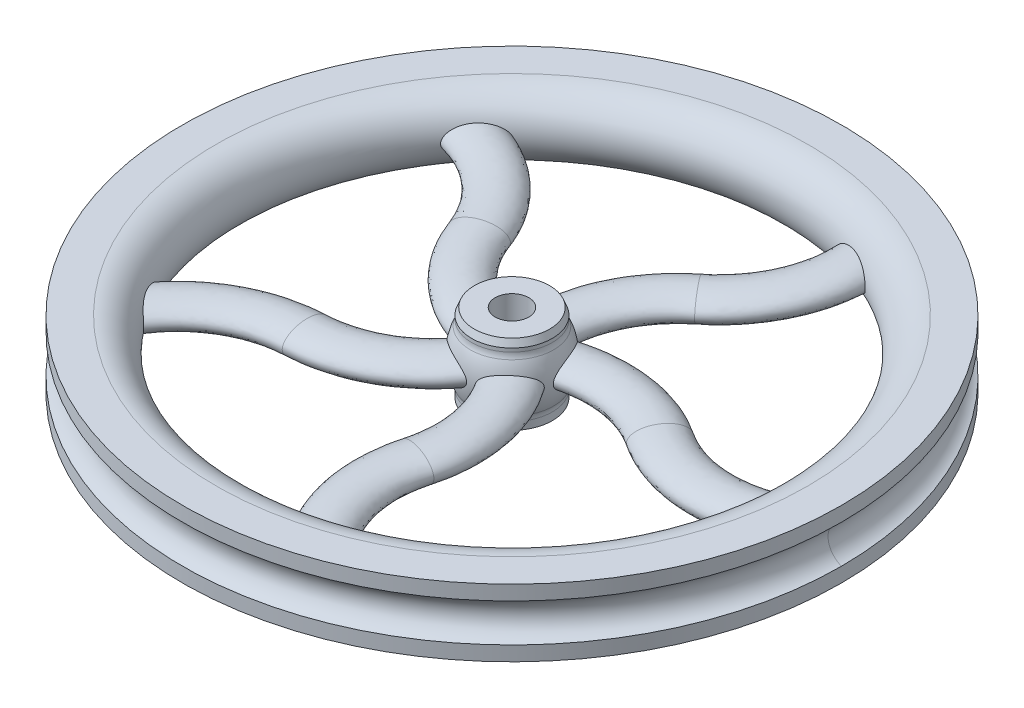
SolidWorks part; units mm, degrees
ref_plane "Front" through (0, 0, 0) normal (0, 0, 1) x (1, 0, 0)
ref_plane "Top" through (0, 0, 0) normal (0, 1, 0) x (1, 0, 0)
ref_plane "Right" through (0, 0, 0) normal (1, 0, 0) x (0, 0, -1)
sketch "Sketch1" plane through (0, 0, 0) normal (0, 0, 1) x (1, 0, 0)
  line L0 (30, -22.3607) -> (30, -30)
  line L5 (0, 30) -> (30, 30)
  line L6 (0, 30) -> (0, -30) construction
  line L7 (0, -30) -> (30, -30)
  line L8 (30, 30) -> (30, 22.3607)
  line L9 (0, 30) -> (0, -30) construction
  line L10 (0, 30) -> (0, -30)
  arc A0 (30.9524, 18.1015) -> (30.9524, -18.1015) centre (-7.5, 0) cw
  arc A1 (30.9524, -18.1015) -> (30, -22.3607) centre (40, -22.3607) ccw
  arc A2 (30.9524, 18.1015) -> (30, 22.3607) centre (40, 22.3607) cw
  point P10 (30, -20)
  point P13 (30, 20)
  dimension "D6" = 10
  dimension "D1" = 10
  dimension "D2" = 5
  dimension "D3" = 40
  dimension "D4" = 60
  dimension "D5" = 60
revolve "Hub" add sketch "Sketch1" angle 360 about L6
sketch "Sketch2" plane through (0, 0, 0) normal (0, 0, 1) x (1, 0, 0)
  line L0 (0, -1000) -> (0, 49000) construction
  line L1 (-1000, 0) -> (914.045, 0) construction
  line L2 (220, 0) -> (914.045, 0) construction
  line L3 (220, 25) -> (245, 25)
  line L4 (220, -25) -> (245, -25)
  line L5 (245, 25) -> (245, 14.1421)
  line L8 (245, -14.1421) -> (245, -25)
  arc A0 (220, 25) -> (220, -25) centre (220, 0) ccw
  arc A2 (245, 14.1421) -> (245, -14.1421) centre (250, 0) ccw
  point P7 (250, 0)
  dimension "D3" = 30
  dimension "D1" = 25
  dimension "D2" = 50
  dimension "D4" = 5
  dimension "D5" = 500
revolve "Rim" add sketch "Sketch2" angle 360 about L0
sketch "Sketch3" plane through (0, 0, 0) normal (0, 1, 0) x (1, 0, 0)
  line L0 (-201000, 0) -> (200914.045, 0) construction
  line L5 (220, 0) -> (245, 0) construction
  arc A0 (0, 0) -> (110, 0) centre (55, -83.5165) cw
  arc A1 (110, 0) -> (220, 0) centre (165, 83.5165) ccw
  circle A2 centre (0, 0) radius 220 construction
  dimension "D1" = 100
ref_plane "Plane1" through (0, 0, 0) normal (0.8352, 0, -0.55) x (-0.55, 0, -0.8352)
sketch "Sketch4" plane through (0, 0, 0) normal (0.8352, 0, -0.55) x (-0.55, 0, -0.8352)
  ellipse E0 centre (0, 0) end of major axis (-18, 0) minor radius 10
  dimension "D1" = 36
  dimension "D2" = 20
sweep "Spoke" add profiles "Sketch4" path "Sketch3"
pattern_circular "CirPattern1" count 5 over 360 about axis through (0, 30, 0) along (0, 1, 0) of "Spoke"
hole_wizard "Ø25.0 (25) Diameter Hole1" positions "Sketch5" profile "Sketch6" hole size "Ø25.0" standard "ANSI Metric" end condition through all
sketch "Sketch5" plane through (0, 30, 0) normal (0, 1, 0) x (1, 0, 0)
  point P0 (0, 0)
sketch "Sketch6" plane through (0, 30, 0) normal (1, 0, 0) x (0, 0, 1)
  line L0 (0, 0) -> (0, 60)
  line L1 (0, 60) -> (12.5, 60)
  line L2 (12.5, 60) -> (12.5, 0)
  line L5 (12.5, 0) -> (0, 0)
  line L11 (0, -6.35) -> (0, 107.95) construction
  dimension "Thru Hole Dia." = 25
  dimension "Thru Hole Depth" = 60
fillet "Fillet1" [suppressed] radius 3
chamfer "Chamfer1" distance 5 distance2 2 1 edges at (0, 30, 30)
chamfer "Chamfer2" distance 5 distance2 2 1 edges at (0, -30, 30)
split line "Split Line1"
